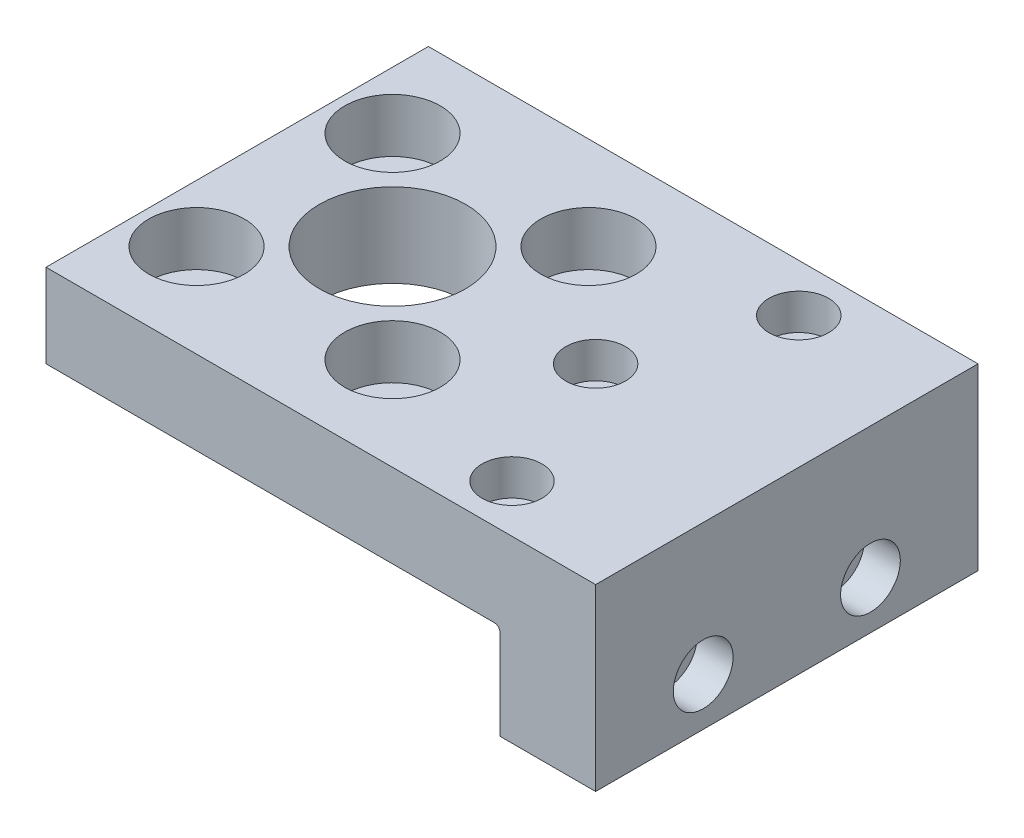
SolidWorks part; units mm, degrees
ref_plane "Front Plane" through (0, 0, 0) normal (0, 0, 1) x (1, 0, 0)
ref_plane "Top Plane" through (0, 0, 0) normal (0, 1, 0) x (1, 0, 0)
ref_plane "Right Plane" through (0, 0, 0) normal (1, 0, 0) x (0, 0, -1)
sketch "Sketch1" plane through (0, 0, 0) normal (0, 1, 0) x (1, 0, 0)
  line L1 (-73.025, -50.8) -> (73.025, -50.8)
  line L2 (-73.025, -50.8) -> (-73.025, 50.8)
  line L3 (-73.025, 50.8) -> (73.025, 50.8)
  line L4 (73.025, -50.8) -> (73.025, 50.8)
  line L5 (-73.025, -50.8) -> (73.025, 50.8) construction
  line L6 (-73.025, 50.8) -> (73.025, -50.8) construction
  point P0 (0, 0)
  dimension "D1" = 73.025
  dimension "D2" = 50.8
extrude "Boss-Extrude1" add sketch "Sketch1" along normal mid plane 22.225
sketch "Sketch2" plane through (0, 0, 0) normal (0, 1, 0) x (1, 0, 0)
  line L1 (47.625, -50.8) -> (73.025, -50.8)
  line L2 (47.625, -50.8) -> (47.625, 50.8)
  line L3 (47.625, 50.8) -> (73.025, 50.8)
  line L4 (73.025, -50.8) -> (73.025, 50.8)
  point P10 (0, 0)
  dimension "D1" = 25.4
  dimension "D2" = 101.6
  dimension "D3" = 73.025
  dimension "D4" = 50.8
extrude "Boss-Extrude2" add sketch "Sketch2" along normal blind 25.4 from offset 36.5125
fillet "Fillet1" radius 1.524 1 edges at (47.625, -11.1125, 0)
sketch "Sketch3" plane through (0, 0, 0) normal (0, 1, 0) x (1, 0, 0)
  circle A0 centre (-31.75, 0) radius 19.4437
  point P2 (0, 0)
  dimension "D1" = 38.8874
  dimension "D2" = 31.75
extrude "Cut-Extrude2" cut sketch "Sketch3" against normal blind 36.5125 from offset 11.1125
sketch "Sketch4" plane through (0, 0, 0) normal (0, 1, 0) x (1, 0, 0)
  circle A0 centre (-57.785, -26.035) radius 6.7437
  circle A1 centre (-5.715, -26.035) radius 6.7437
  circle A2 centre (-57.785, 26.035) radius 6.7437
  circle A3 centre (-5.715, 26.035) radius 6.7437
  point P8 (0, 0)
  dimension "D1" = 13.4874
  dimension "D2" = 13.4874
  dimension "D3" = 13.4874
  dimension "D4" = 13.4874
  dimension "D5" = 52.07
  dimension "D6" = 52.07
  dimension "D7" = 57.785
  dimension "D8" = 26.035
extrude "Cut-Extrude4" cut sketch "Sketch4" against normal through all from offset 11.1125
sketch "Sketch5" plane through (0, 0, 0) normal (0, 1, 0) x (1, 0, 0)
  circle A0 centre (-57.785, -26.035) radius 12.7
  circle A1 centre (-5.715, -26.035) radius 12.7
  circle A2 centre (-57.785, 26.035) radius 12.7
  circle A3 centre (-5.715, 26.035) radius 12.7
  point P8 (0, 0)
  dimension "D1" = 25.4
  dimension "D2" = 25.4
  dimension "D3" = 25.4
  dimension "D4" = 25.4
  dimension "D5" = 52.07
  dimension "D6" = 52.07
  dimension "D7" = 57.785
  dimension "D8" = 26.035
extrude "Cut-Extrude6" cut sketch "Sketch5" against normal blind 14.2875 from offset 11.1125
sketch "Sketch6" plane through (0, 0, 0) normal (0, 1, 0) x (1, 0, 0)
  circle A0 centre (38.1, -38.1) radius 5.1562
  circle A1 centre (38.1, 38.1) radius 5.1562
  point P4 (0, 0)
  dimension "D1" = 10.3124
  dimension "D2" = 10.3124
  dimension "D3" = 76.2
  dimension "D4" = 38.1
  dimension "D5" = 38.1
extrude "Cut-Extrude8" cut sketch "Sketch6" against normal through all from offset 11.1125
sketch "Sketch7" plane through (0, 0, 0) normal (0, 1, 0) x (1, 0, 0)
  circle A0 centre (38.1, -38.1) radius 7.9375
  circle A1 centre (38.1, 38.1) radius 7.9375
  point P4 (0, 0)
  dimension "D1" = 15.875
  dimension "D2" = 15.875
  dimension "D3" = 76.2
  dimension "D4" = 38.1
  dimension "D5" = 38.1
extrude "Cut-Extrude10" cut sketch "Sketch7" against normal blind 9.525 from offset 11.1125
sketch "Sketch8" plane through (0, 0, 0) normal (0, 1, 0) x (1, 0, 0)
  circle A0 centre (22.225, 0) radius 5.1562
  point P2 (0, 0)
  dimension "D1" = 10.3124
  dimension "D2" = 22.225
extrude "Cut-Extrude12" cut sketch "Sketch8" against normal through all from offset 11.1125
sketch "Sketch9" plane through (0, 0, 0) normal (0, 1, 0) x (1, 0, 0)
  circle A0 centre (22.225, 0) radius 7.9375
  point P2 (0, 0)
  dimension "D1" = 15.875
  dimension "D2" = 22.225
extrude "Cut-Extrude14" cut sketch "Sketch9" against normal blind 9.525 from offset 11.1125
sketch "Sketch10" plane through (0, 0, 0) normal (1, 0, 0) x (0, 0, -1)
  circle A0 centre (-22.225, -23.8125) radius 5.1562
  circle A1 centre (22.225, -23.8125) radius 5.1562
  point P4 (0, 0)
  dimension "D1" = 10.3124
  dimension "D2" = 10.3124
  dimension "D3" = 44.45
  dimension "D4" = 22.225
  dimension "D5" = 23.8125
extrude "Cut-Extrude16" cut sketch "Sketch10" against normal through all from offset 73.025
sketch "Sketch11" plane through (0, 0, 0) normal (1, 0, 0) x (0, 0, -1)
  circle A0 centre (-22.225, -23.8125) radius 7.9375
  circle A1 centre (22.225, -23.8125) radius 7.9375
  point P4 (0, 0)
  dimension "D1" = 15.875
  dimension "D2" = 15.875
  dimension "D3" = 44.45
  dimension "D4" = 22.225
  dimension "D5" = 23.8125
extrude "Cut-Extrude18" cut sketch "Sketch11" against normal blind 9.525 from offset 73.025
